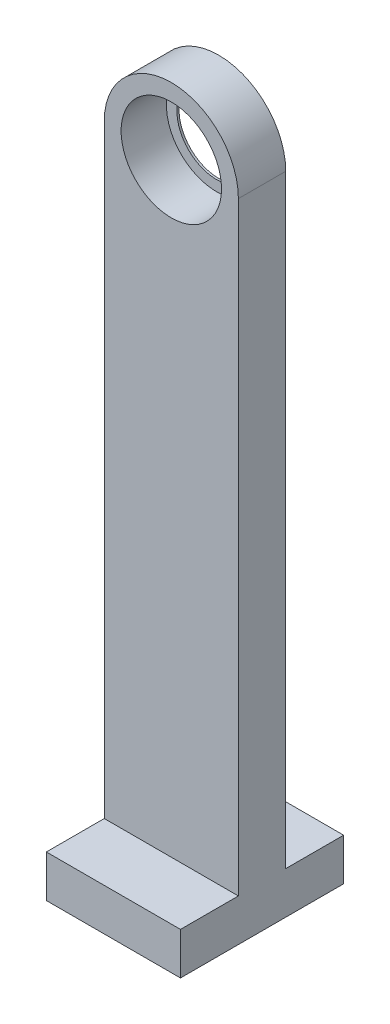
SolidWorks part; units mm, degrees
ref_plane "Front Plane" through (0, 0, 0) normal (0, 0, 1) x (1, 0, 0)
ref_plane "Top Plane" through (0, 0, 0) normal (0, 1, 0) x (1, 0, 0)
ref_plane "Right Plane" through (0, 0, 0) normal (1, 0, 0) x (0, 0, -1)
sketch "Sketch1" plane through (0, 0, 0) normal (0, 0, 1) x (1, 0, 0)
  circle A0 centre (0, 0) radius 4.77
  circle A1 centre (0, 0) radius 6.3701
  dimension "D1" = 9.54
extrude "Boss-Extrude1" add sketch "Sketch1" along normal blind 4.5
sketch "Sketch3" plane through (0, 0, 0) normal (0, 0, 1) x (1, 0, 0)
  line L1 (6.3701, 0) -> (6.3701, -61.37)
  line L2 (6.3701, -61.37) -> (-6.3701, -61.37)
  line L3 (-6.3701, -61.37) -> (-6.3701, 0)
  circle A0 centre (0, 0) radius 6.3701 construction
  arc A1 (6.3701, 0) -> (-6.3701, 0) centre (0, 0) cw
  dimension "D1" = 61.37
extrude "Boss-Extrude2" add sketch "Sketch3" along normal blind 4.5 contours L1 A1 L3 L2
sketch "Sketch4" plane through (0, 0, 0) normal (0, 0, 1) x (1, 0, 0)
  line L0 (6.3701, -61.37) -> (6.3701, -57.37)
  line L1 (6.3701, 0) -> (6.3701, -61.37) construction
  line L2 (6.3701, -57.37) -> (-6.3701, -57.37)
  line L3 (-6.3701, -61.37) -> (-6.3701, 0) construction
  line L4 (-6.3701, -57.37) -> (-6.3701, -61.37)
  line L5 (6.3701, -61.37) -> (-6.3701, -61.37) construction
  line L6 (-6.3701, -61.37) -> (6.3701, -61.37)
  dimension "D1" = 4
extrude "Boss-Extrude3" add sketch "Sketch4" along normal blind 10 and the other way blind 5.5
sketch "Sketch6" plane through (0, 0, 0) normal (0, 0, 1) x (1, 0, 0)
  circle A0 centre (0, 0) radius 3.77
  circle A1 centre (0, 0) radius 4.77 construction
  circle A2 centre (0, 0) radius 4.77
  dimension "D1" = 1
extrude "Boss-Extrude4" add sketch "Sketch6" along normal blind 0.2
